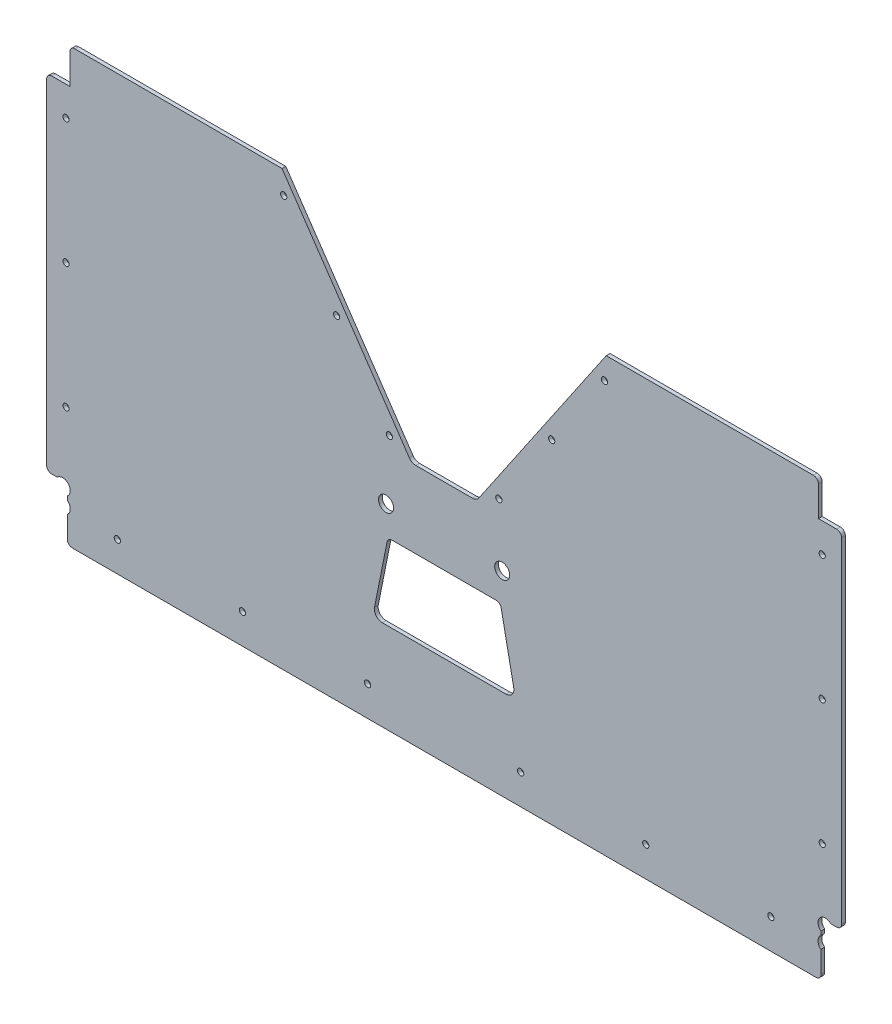
SolidWorks part; units mm, degrees
ref_plane "前视基准面" through (0, 0, 0) normal (0, 0, 1) x (1, 0, 0)
ref_plane "上视基准面" through (0, 0, 0) normal (0, 1, 0) x (1, 0, 0)
ref_plane "右视基准面" through (0, 0, 0) normal (1, 0, 0) x (0, 0, -1)
sketch "草图1" plane through (0, 0, 0) normal (0, 0, 1) x (1, 0, 0)
  line L0 (64.593, -287.2749) -> (-37.1214, -436.5804)
  line L1 (-42.3693, -439.3552) -> (-87.5654, -439.3552)
  line L2 (-92.8133, -436.5804) -> (-194.5277, -287.2749)
  line L3 (-120.5983, -553.9996) -> (-117.8883, -540.4499)
  line L4 (-15.5631, -561.5949) -> (-114.3716, -561.5949)
  line L5 (-9.3364, -553.9996) -> (-12.0463, -540.4499)
  line L14 (-16.3413, -518.9753) -> (-20.0249, -500.5573)
  line L15 (-22.5607, -496.6354) -> (-61.2765, -468.9813)
  line L16 (-107.374, -496.6354) -> (-68.6582, -468.9813)
  line L17 (-113.5934, -518.9753) -> (-109.9098, -500.5573)
  line L18 (246.1827, -287.2749) -> (246.1827, -612.3949)
  line L19 (239.8327, -618.7449) -> (-369.7673, -618.7449)
  line L20 (-376.1173, -287.2749) -> (-376.1173, -612.3949)
  line L21 (-376.1173, -287.2749) -> (-194.5277, -287.2749)
  line L22 (64.593, -287.2749) -> (246.1827, -287.2749)
  line L23 (-64.9673, -439.3552) -> (-64.9673, -618.7449) construction
  line L24 (-16.3413, -518.9753) -> (-12.0463, -540.4499)
  line L25 (-113.5934, -518.9753) -> (-117.8883, -540.4499)
  arc A0 (-42.3693, -439.3552) -> (-37.1214, -436.5804) centre (-42.3693, -433.0052) ccw
  arc A1 (-92.8133, -436.5804) -> (-87.5654, -439.3552) centre (-87.5654, -433.0052) ccw
  arc A5 (-120.5983, -553.9996) -> (-114.3716, -561.5949) centre (-114.3716, -555.2449) ccw
  arc A6 (-15.5631, -561.5949) -> (-9.3364, -553.9996) centre (-15.5631, -555.2449) ccw
  arc A10 (-20.0249, -500.5573) -> (-22.5607, -496.6354) centre (-26.2516, -501.8026) ccw
  arc A11 (-61.2765, -468.9813) -> (-68.6582, -468.9813) centre (-64.9673, -474.1485) ccw
  arc A24 (-107.374, -496.6354) -> (-109.9098, -500.5573) centre (-103.6831, -501.8026) ccw
  circle A26 centre (-111.3712, -477.7682) radius 6
  circle A27 centre (-18.5635, -477.7682) radius 6
  circle A29 centre (239.8327, -607.6324) radius 6
  circle A30 centre (239.8327, -594.9324) radius 6
  arc A31 (239.8327, -618.7449) -> (246.1827, -612.3949) centre (239.8327, -612.3949) ccw
  arc A32 (-376.1173, -612.3949) -> (-369.7673, -618.7449) centre (-369.7673, -612.3949) ccw
  circle A33 centre (-369.7673, -607.6324) radius 6
  circle A34 centre (-369.7673, -594.9324) radius 6
  dimension "D1" = 331.47
  dimension "D2" = 12
  dimension "D5" = 180.6597
extrude "凸台-拉伸1" add sketch "草图1" along normal blind 3
sketch "草图2" plane through (0, 0, 3) normal (0, 0, 1) x (1, 0, 0)
  line L5 (-64.9673, -618.7449) -> (-64.9673, -439.3552) construction
  line L6 (-369.7673, -618.7449) -> (239.8327, -618.7449) construction
  line L7 (-42.3693, -439.3552) -> (-87.5654, -439.3552) construction
  line L8 (246.1827, -287.2749) -> (234.1827, -287.2749)
  line L9 (-376.1173, -287.2749) -> (-364.1173, -287.2749)
  line L10 (-376.1173, -287.2749) -> (-376.1173, -315.2749)
  line L11 (-376.1173, -315.2749) -> (-364.1173, -315.2749)
  line L12 (-364.1173, -287.2749) -> (-364.1173, -315.2749)
  line L13 (246.1827, -287.2749) -> (246.1827, -315.2749)
  line L14 (246.1827, -315.2749) -> (234.1827, -315.2749)
  line L15 (234.1827, -287.2749) -> (234.1827, -315.2749)
  line L16 (-376.1173, -287.2749) -> (-376.1173, -612.3949) construction
  line L19 (-376.1173, -590.7449) -> (-366.1173, -590.7449)
  line L20 (-376.1173, -590.7449) -> (-376.1173, -618.7449)
  line L21 (-376.1173, -618.7449) -> (-366.1173, -618.7449)
  line L22 (-366.1173, -590.7449) -> (-366.1173, -618.7449)
  line L23 (246.1827, -590.7449) -> (236.1827, -590.7449)
  line L24 (246.1827, -590.7449) -> (246.1827, -618.7449)
  line L25 (246.1827, -618.7449) -> (236.1827, -618.7449)
  line L26 (236.1827, -590.7449) -> (236.1827, -618.7449)
  line L27 (-92.8133, -436.5804) -> (-194.5277, -287.2749) construction
  line L28 (-193.1552, -305.2749) -> (-108.7027, -429.2418) construction
  line L29 (-194.5277, -287.2749) -> (-376.1173, -287.2749) construction
  line L30 (-367.1173, -538.7449) -> (-367.1173, -338.7449) construction
  line L31 (-326.1173, -609.7449) -> (-126.1173, -609.7449) construction
  circle A0 centre (-193.1552, -305.2749) radius 2.5
  circle A1 centre (-108.7027, -429.2418) radius 2.5
  circle A2 centre (-150.9289, -367.2584) radius 2.5
  circle A3 centre (-326.1173, -609.7449) radius 2.5
  circle A5 centre (-367.1173, -338.7449) radius 2.5
  circle A6 centre (-367.1173, -538.7449) radius 2.5
  circle A7 centre (-367.1173, -438.7449) radius 2.5
  circle A8 centre (-126.1173, -609.7449) radius 2.5
  circle A9 centre (-226.1173, -609.7449) radius 2.5
  circle A10 centre (-21.232, -429.2418) radius 2.5
  circle A11 centre (20.9942, -367.2584) radius 2.5
  circle A12 centre (63.2205, -305.2749) radius 2.5
  circle A13 centre (237.1827, -338.7449) radius 2.5
  circle A14 centre (237.1827, -438.7449) radius 2.5
  circle A15 centre (237.1827, -538.7449) radius 2.5
  circle A16 centre (196.1827, -609.7449) radius 2.5
  circle A17 centre (96.1827, -609.7449) radius 2.5
  circle A18 centre (-3.8173, -609.7449) radius 2.5
  point P50 (-137.2506, -593.0053)
  dimension "D5" = 5
  dimension "D13" = 100
  dimension "D14" = 100
  dimension "D1" = 12
  dimension "D2" = 28
  dimension "D3" = 10
  dimension "D4" = 28
  dimension "D6" = 9
  dimension "D7" = 150
  dimension "D8" = 18
  dimension "D9" = 9
  dimension "D10" = 100
  dimension "D11" = 100
  dimension "D12" = 80
  dimension "D16" = 9
  dimension "D17" = 50
extrude "切除-拉伸1" cut sketch "草图2" against normal through all
sketch "草图3" plane through (0, 0, 3) normal (0, 0, 1) x (1, 0, 0)
  line L0 (-109.9098, -500.5573) -> (-20.0249, -500.5573)
  line L1 (-20.0249, -500.5573) -> (-20.0249, -490.6631)
  line L2 (-20.0249, -490.6631) -> (-58.0771, -460.6799)
  line L3 (-58.0771, -460.6799) -> (-109.0155, -490.6631)
  line L4 (-109.0155, -490.6631) -> (-109.9098, -500.5573)
  line L5 (-64.9673, -439.3552) -> (-64.9673, -618.7449) construction
  line L6 (-376.1173, -315.2749) -> (-382.6173, -315.2749)
  line L7 (-376.1173, -315.2749) -> (-376.1173, -590.7449)
  line L8 (-376.1173, -590.7449) -> (-382.6173, -590.7449)
  line L9 (-382.6173, -315.2749) -> (-382.6173, -590.7449)
  line L10 (-42.3693, -439.3552) -> (-87.5654, -439.3552) construction
  line L11 (-366.1173, -618.7449) -> (236.1827, -618.7449) construction
  line L12 (252.6827, -315.2749) -> (252.6827, -590.7449)
  line L13 (246.1827, -590.7449) -> (252.6827, -590.7449)
  line L14 (246.1827, -315.2749) -> (246.1827, -590.7449)
  line L15 (246.1827, -315.2749) -> (252.6827, -315.2749)
  dimension "D1" = 6.5
extrude "凸台-拉伸2" add sketch "草图3" against normal blind 3
sketch "草图4" plane through (0, 0, 3) normal (0, 0, 1) x (1, 0, 0)
  line L1 (-366.1173, -618.7449) -> (236.1827, -618.7449)
  line L2 (-366.1173, -618.7449) -> (-366.1173, -633.7449)
  line L3 (-366.1173, -633.7449) -> (236.1827, -633.7449)
  line L4 (236.1827, -618.7449) -> (236.1827, -633.7449)
  point P5 (231.1827, -618.7449)
  dimension "D1" = 15
extrude "凸台-拉伸3" add sketch "草图4" against normal blind 3
fillet "圆角1" radius 4 10 edges at (236.1827, -633.7449, 1.5) (252.6827, -590.7449, 1.5) (252.6827, -315.2749, 1.5) (234.1827, -287.2749, 1.5) (-20.0249, -500.5573, 1.5) (-109.9098, -500.5573, 1.5) (-382.6173, -315.2749, 1.5) (-364.1173, -287.2749, 1.5) (-382.6173, -590.7449, 1.5) (-366.1173, -633.7449, 1.5)
